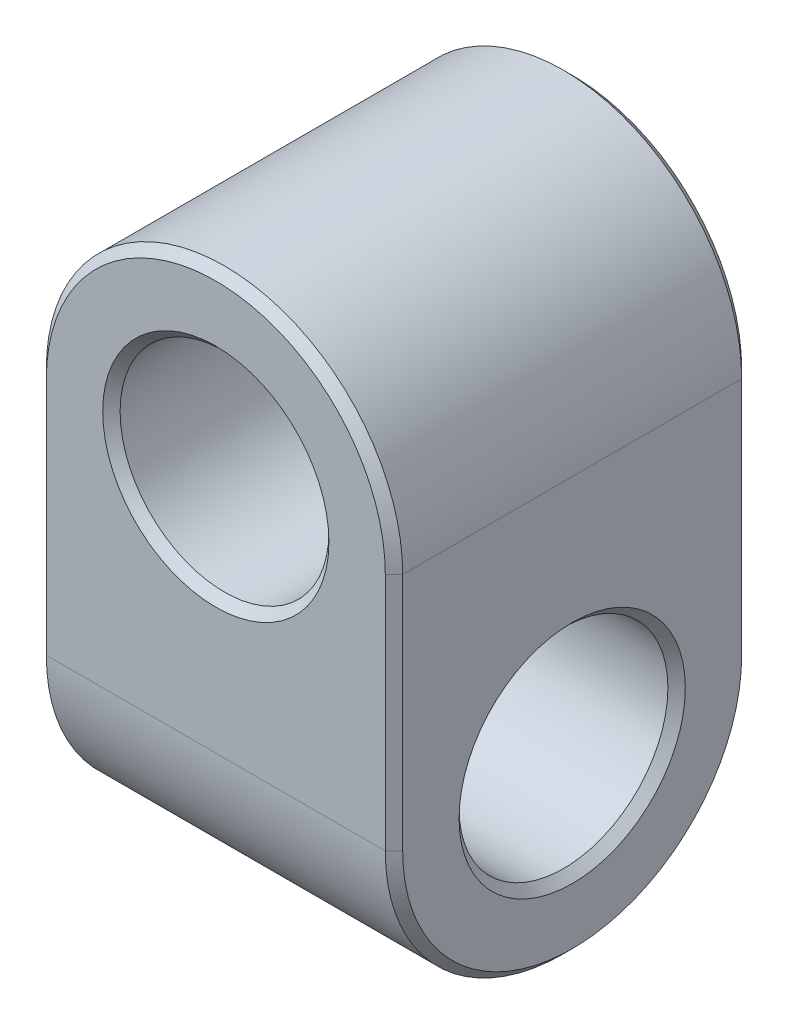
SolidWorks part; units mm, degrees
ref_plane "Front Plane" through (0, 0, 0) normal (0, 0, 1) x (1, 0, 0)
ref_plane "Top Plane" through (0, 0, 0) normal (0, 1, 0) x (1, 0, 0)
ref_plane "Right Plane" through (0, 0, 0) normal (1, 0, 0) x (0, 0, -1)
sketch "Sketch1" plane through (0, 0, 0) normal (0, 0, 1) x (1, 0, 0)
  line L1 (-8.128, 9.525) -> (8.128, 9.525) construction
  line L2 (-8.128, 9.525) -> (-8.128, -9.525)
  line L3 (-8.128, -9.525) -> (8.128, -9.525)
  line L4 (8.128, 9.525) -> (8.128, -9.525)
  line L5 (-8.128, 9.525) -> (8.128, -9.525) construction
  line L6 (-8.128, -9.525) -> (8.128, 9.525) construction
  arc A0 (-8.128, 9.525) -> (8.128, 9.525) centre (0, 9.525) cw
  circle A1 centre (0, 9.525) radius 4.7625
  point P0 (0, 0)
  dimension "D1" = 8.128
  dimension "D2" = 9.525
  dimension "D3" = 19.05
extrude "Boss-Extrude1" add sketch "Sketch1" along normal blind 16.256
sketch "Sketch2" plane through (8.128, 0, 0) normal (1, 0, 0) x (0, 0, -1)
  line L0 (-16.256, -1.397) -> (0, -1.397) construction
  line L1 (-16.256, -9.525) -> (-16.256, 9.525) construction
  line L2 (0, -9.525) -> (0, 9.525) construction
  line L3 (-16.256, -9.525) -> (0, -9.525) construction
  line L4 (-16.256, -9.525) -> (-16.256, 9.525) construction
  line L5 (-16.256, -1.397) -> (-16.256, -9.525)
  line L6 (-16.256, -9.525) -> (0, -9.525)
  line L7 (0, -9.525) -> (0, -1.397)
  arc A0 (0, -1.397) -> (-16.256, -1.397) centre (-8.128, -1.397) cw
  circle A1 centre (-8.128, -1.397) radius 4.7625
  line M3 (0, -9.525) -> (0, 9.525)
  line M5 (-16.256, 9.525) -> (-16.256, -9.525)
  line M6 (-16.256, -9.525) -> (0, -9.525)
  dimension "D1" = 9.525
extrude "Cut-Extrude1" cut sketch "Sketch2" against normal up to surface (16.256 mm away) contours A0 L6 M3 | A0 M6 M5 | A1 up to face at (-8.128, 0, 8.128)
chamfer "Chamfer1" distance 0.3969 angle 45 11 edges at (-8.128, 3.3655, 8.128) (4.7625, 9.525, 16.256) (8.128, 3.3655, 8.128) (-8.128, 4.064, 0) (0, 17.653, 0) (-8.128, -9.525, 8.128) (8.128, 4.064, 0) (-8.128, 4.064, 16.256) (8.128, -9.525, 8.128) (0, 17.653, 16.256) (8.128, 4.064, 16.256)
